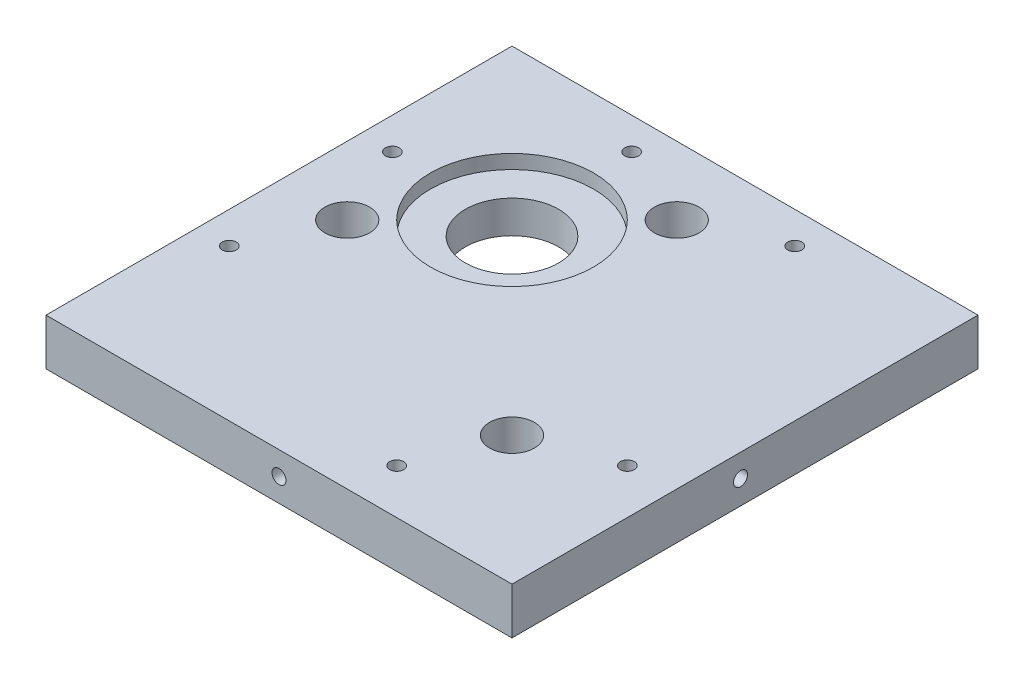
SolidWorks part; units mm, degrees
ref_plane "前视基准面" through (0, 0, 0) normal (0, 0, 1) x (1, 0, 0)
ref_plane "上视基准面" through (0, 0, 0) normal (0, 1, 0) x (1, 0, 0)
ref_plane "右视基准面" through (0, 0, 0) normal (1, 0, 0) x (0, 0, -1)
sketch "Sketch1" plane through (0, 0, 0) normal (0, 1, 0) x (1, 0, 0)
  line L1 (-50, 50) -> (50, 50)
  line L2 (-50, 50) -> (-50, -50)
  line L3 (-50, -50) -> (50, -50)
  line L4 (50, 50) -> (50, -50)
  line L5 (-50, 50) -> (50, -50) construction
  line L6 (-50, -50) -> (50, 50) construction
  point P0 (0, 0)
  dimension "D1" = 100
  dimension "D2" = 100
extrude "Boss-Extrude1" add sketch "Sketch1" along normal blind 10
sketch "Sketch2" plane through (0, 10, 0) normal (0, 1, 0) x (1, 0, 0)
  line L0 (-50, 50) -> (50, -50) construction
  circle A0 centre (-17.6777, 17.6777) radius 17.5
  dimension "D1" = 35
  dimension "D2" = 25
extrude "Cut-Extrude1" cut sketch "Sketch2" against normal blind 3
sketch "Sketch3" plane through (0, 10, 0) normal (0, 1, 0) x (1, 0, 0)
  line L0 (-50, 50) -> (50, -50) construction
sketch "Sketch4" plane through (0, 7, 0) normal (0, 1, 0) x (1, 0, 0)
  line L0 (-17.6777, 35.1777) -> (-17.6777, 0.1777) construction
  circle A0 centre (-17.6777, 17.6777) radius 17.5 construction
  circle A1 centre (-17.6777, 17.6777) radius 17.5 construction
  circle A2 centre (-17.6777, 17.6777) radius 10
  dimension "D1" = 20
extrude "Cut-Extrude2" cut sketch "Sketch4" against normal blind 7
sketch "Sketch5" plane through (0, 10, 0) normal (0, 1, 0) x (1, 0, 0)
  line L0 (50, -50) -> (-50, 50) construction
  line L1 (-50, 50) -> (-17.6777, 17.6777) construction
  line L2 (-17.6777, 17.6777) -> (-17.6777, 50) construction
  line L3 (50, 50) -> (-50, 50) construction
  line L4 (-17.6777, 50) -> (-17.6777, 0.1777) construction
  line L5 (-17.6777, 0.1777) -> (-0.1777, 17.6777) construction
  line L6 (-0.1777, 17.6777) -> (-35.1777, 17.6777) construction
  line L7 (-35.1777, 17.6777) -> (-24.7487, 10.6066) construction
  line L8 (-24.7487, 10.6066) -> (-50, -14.6447) construction
  line L9 (-50, 50) -> (-50, -50) construction
  line L10 (-50, -14.6447) -> (14.6447, 50) construction
  line L11 (14.6447, 50) -> (-37.3744, -2.019) construction
  line L12 (-37.3744, -2.019) -> (-37.3744, 50) construction
  circle A0 centre (-17.6777, 17.6777) radius 17.5 construction
  circle A1 centre (-17.6777, 17.6777) radius 17.5 construction
  circle A2 centre (-17.6777, 17.6777) radius 10 construction
  circle A3 centre (-35.3553, 0) radius 4.8
  circle A4 centre (0, 35.3553) radius 4.8
  dimension "D1" = 9.6
  dimension "D2" = 25
extrude "Cut-Extrude3" cut sketch "Sketch5" against normal blind 20
sketch "Sketch6" plane through (0, 10, 0) normal (0, 1, 0) x (1, 0, 0)
  line L0 (50, -50) -> (-50, 50) construction
  line L1 (-50, 50) -> (-17.6777, 17.6777) construction
  line L2 (-17.6777, 17.6777) -> (-17.6777, 50) construction
  line L3 (50, 50) -> (-50, 50) construction
  line L4 (-17.6777, 50) -> (-17.6777, -50) construction
  line L5 (-50, -50) -> (50, -50) construction
  line L6 (-17.6777, -50) -> (-0.1777, 17.6777) construction
  line L7 (-0.1777, 17.6777) -> (-35.1777, 17.6777) construction
  line L8 (-35.1777, 17.6777) -> (-35.3553, 0) construction
  line L9 (-35.3553, 0) -> (-35.3553, 50) construction
  line L10 (-35.3553, 50) -> (-35.3553, -50) construction
  line L11 (-35.3553, 0) -> (-50, 0) construction
  line L12 (-50, 50) -> (-50, -50) construction
  circle A0 centre (-17.6777, 17.6777) radius 17.5 construction
  circle A1 centre (-17.6777, 17.6777) radius 17.5 construction
  circle A2 centre (-43.1799, 17.5) radius 1.5
  circle A3 centre (-43.1799, -17.5) radius 1.5
  circle A4 centre (17.5, 43.1799) radius 1.5
  circle A5 centre (-17.5, 43.1799) radius 1.5
  dimension "D1" = 3
  dimension "D2" = 8
  dimension "D3" = 17.5
extrude "Cut-Extrude4" cut sketch "Sketch6" against normal blind 5
sketch "Sketch7" plane through (0, 10, 0) normal (0, 1, 0) x (1, 0, 0)
  line L0 (-50, 50) -> (50, -50) construction
  line L1 (50, -50) -> (-17.6777, 17.6777) construction
  line L2 (-17.6777, 17.6777) -> (14.3871, 49.7425) construction
  line L3 (14.3871, 49.7425) -> (50, 14.1296) construction
  line L4 (50, -50) -> (50, 50) construction
  line L5 (50, 14.1296) -> (17.9352, -17.9352) construction
  line L6 (17.9352, -17.9352) -> (-14.1296, -50) construction
  line L7 (-50, -50) -> (50, -50) construction
  circle A0 centre (22.3223, -22.3223) radius 4.8
  dimension "D2" = 9.6
  dimension "D1" = 40
extrude "Cut-Extrude5" cut sketch "Sketch7" against normal blind 10
sketch "Sketch8" plane through (0, 10, 0) normal (0, 1, 0) x (1, 0, 0)
  line L0 (50, -50) -> (-50, 50) construction
  line L1 (-50, 50) -> (-17.6777, 17.6777) construction
  line L2 (-17.6777, 17.6777) -> (-50, -14.6447) construction
  line L3 (-50, 50) -> (-50, -50) construction
  line L4 (-50, -14.6447) -> (14.6447, 50) construction
  line L5 (50, 50) -> (-50, 50) construction
  line L6 (14.6447, 50) -> (50, 14.6447) construction
  line L7 (50, -50) -> (50, 50) construction
  line L8 (50, 14.6447) -> (-14.6447, -50) construction
  line L9 (-50, -50) -> (50, -50) construction
  line L10 (-14.6447, -50) -> (22.3223, -22.3223) construction
  line L11 (22.3223, -22.3223) -> (50, 5.3553) construction
  line L12 (50, 5.3553) -> (-5.3553, -50) construction
  circle A0 centre (40.3536, -15.6048) radius 1.5
  circle A1 centre (15.6048, -40.3536) radius 1.5
  dimension "D1" = 3
  dimension "D2" = 8
  dimension "D3" = 17.5
extrude "Cut-Extrude6" cut sketch "Sketch8" against normal blind 5
sketch "Sketch9" plane through (50, 0, 0) normal (1, 0, 0) x (0, 0, -1)
  line L0 (50, 0) -> (-50, 10) construction
  line L1 (-50, 10) -> (-50, 0) construction
  line L2 (-50, 0) -> (50, 10) construction
  circle A0 centre (-0.9633, 5.0963) radius 1.5
  dimension "D1" = 3
extrude "Cut-Extrude7" cut sketch "Sketch9" against normal blind 5
sketch "Sketch10" plane through (0, 0, -50) normal (0, 0, -1) x (-1, 0, 0)
  line L0 (50, 0) -> (-50, 10) construction
  line L1 (-50, 10) -> (50, 10) construction
  line L2 (50, 10) -> (-50, 0) construction
  circle A0 centre (0, 5) radius 1.5
  dimension "D1" = 3
extrude "Cut-Extrude8" cut sketch "Sketch10" against normal blind 5
sketch "Sketch11" plane through (-50, 0, 0) normal (-1, 0, 0) x (0, 0, 1)
  line L0 (-50, 10) -> (50, 0) construction
  line L1 (50, 0) -> (50, 10) construction
  line L2 (50, 10) -> (-50, 0) construction
  circle A0 centre (0, 5) radius 1.5
  dimension "D1" = 3
extrude "Cut-Extrude9" cut sketch "Sketch11" against normal blind 5
sketch "Sketch12" plane through (0, 0, 50) normal (0, 0, 1) x (1, 0, 0)
  line L0 (50, 0) -> (-50, 10) construction
  line L1 (50, 10) -> (50, 0) construction
  line L2 (-50, 10) -> (50, 10) construction
  line L3 (50, 10) -> (-50, 0) construction
  circle A0 centre (0, 5) radius 1.5
  dimension "D1" = 3
extrude "Cut-Extrude10" cut sketch "Sketch12" against normal blind 5
